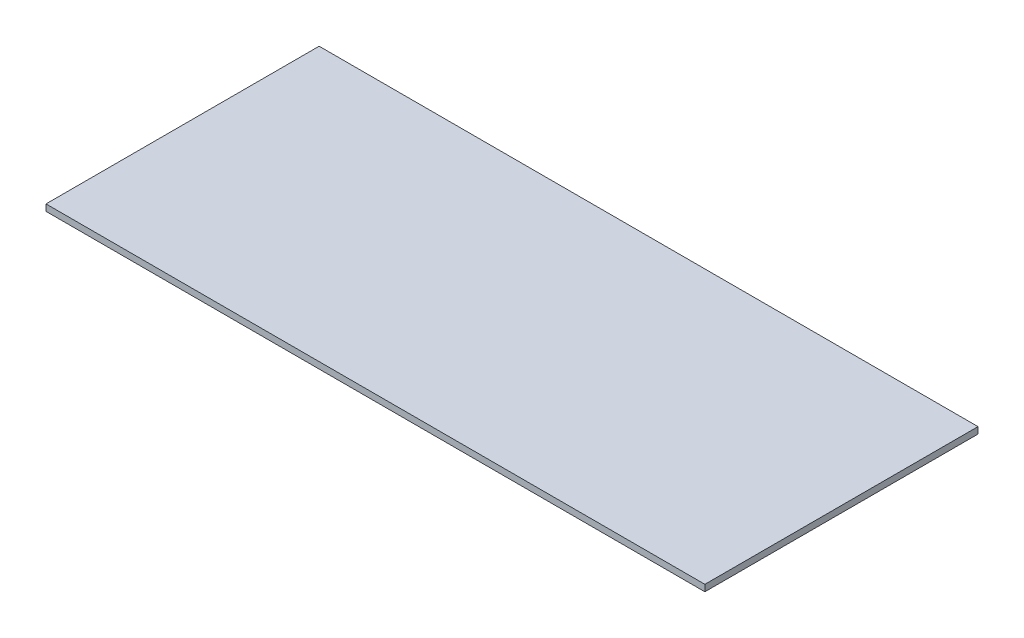
SolidWorks part; units mm, degrees
material "Pine"
ref_plane "Front Plane" through (0, 0, 0) normal (0, 0, 1) x (1, 0, 0)
ref_plane "Top Plane" through (0, 0, 0) normal (0, 1, 0) x (1, 0, 0)
ref_plane "Right Plane" through (0, 0, 0) normal (1, 0, 0) x (0, 0, -1)
sketch "Sketch1" plane through (0, 0, 0) normal (0, 1, 0) x (1, 0, 0)
  line L1 (0, 0) -> (1289.6, 0)
  line L2 (0, 0) -> (0, 534.6)
  line L3 (0, 534.6) -> (1289.6, 534.6)
  line L4 (1289.6, 0) -> (1289.6, 534.6)
  dimension "D1" = 1289.6
  dimension "D2" = 534.6
extrude "Boss-Extrude1" add sketch "Sketch1" along normal blind 12.7
